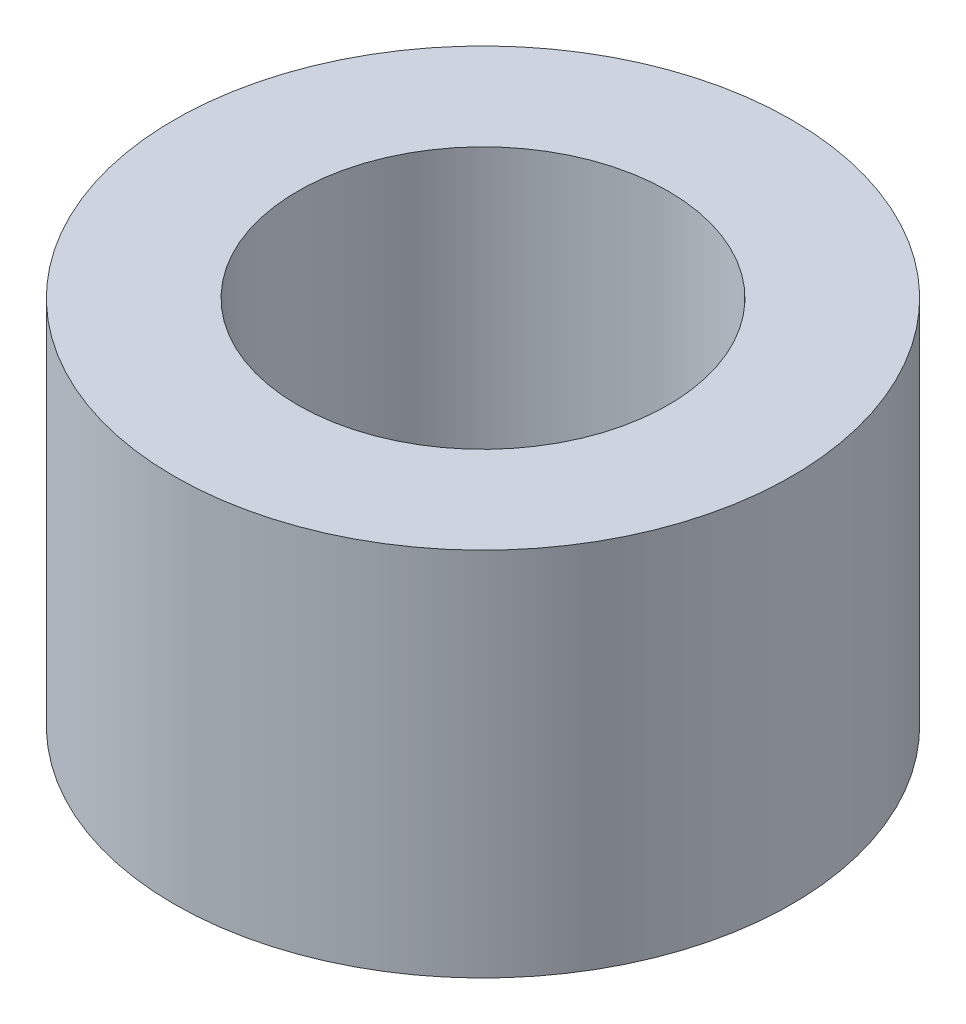
SolidWorks part; units mm, degrees
ref_plane "Front Plane" through (0, 0, 0) normal (0, 0, 1) x (1, 0, 0)
ref_plane "Top Plane" through (0, 0, 0) normal (0, 1, 0) x (1, 0, 0)
ref_plane "Right Plane" through (0, 0, 0) normal (1, 0, 0) x (0, 0, -1)
sketch "Sketch1" plane through (0, 0, 0) normal (0, 1, 0) x (1, 0, 0)
  circle A0 centre (0, 0) radius 1.5
  circle A1 centre (0, 0) radius 2.5
  dimension "D1" = 3
  dimension "D2" = 5
extrude "Boss-Extrude1" add sketch "Sketch1" along normal blind 3
